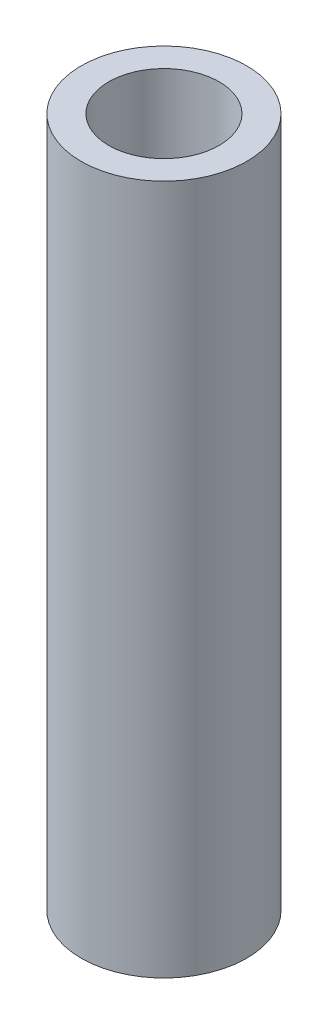
SolidWorks part; units mm, degrees
ref_plane "Přední rovina" through (0, 0, 0) normal (0, 0, 1) x (1, 0, 0)
ref_plane "Horní rovina" through (0, 0, 0) normal (0, 1, 0) x (1, 0, 0)
ref_plane "Pravá rovina" through (0, 0, 0) normal (1, 0, 0) x (0, 0, -1)
sketch "Skica1" plane through (0, 0, 0) normal (1, 0, 0) x (0, 0, -1)
  line L0 (0, 13.4683) -> (0, -11.5317) construction
  line L1 (0, 13.4683) -> (1, 13.4683) construction
  line L2 (1, 13.4683) -> (3, 13.4683)
  line L3 (3, 13.4683) -> (3, -11.5317)
  line L4 (3, -11.5317) -> (1, -11.5317)
  line L5 (1, -11.5317) -> (1, 13.4683)
  dimension "D1" = 25
  dimension "D2" = 1
  dimension "D3" = 2
  dimension "D4" = 25
revolve "Rotovat1" add sketch "Skica1" angle 360 about L0
sketch "Skica2" plane through (0, 13.4683, 0) normal (0, 1, 0) x (1, 0, 0)
  circle A0 centre (0, 0) radius 2
extrude "Odebrat vysunutím1" cut sketch "Skica2" against normal blind 10
